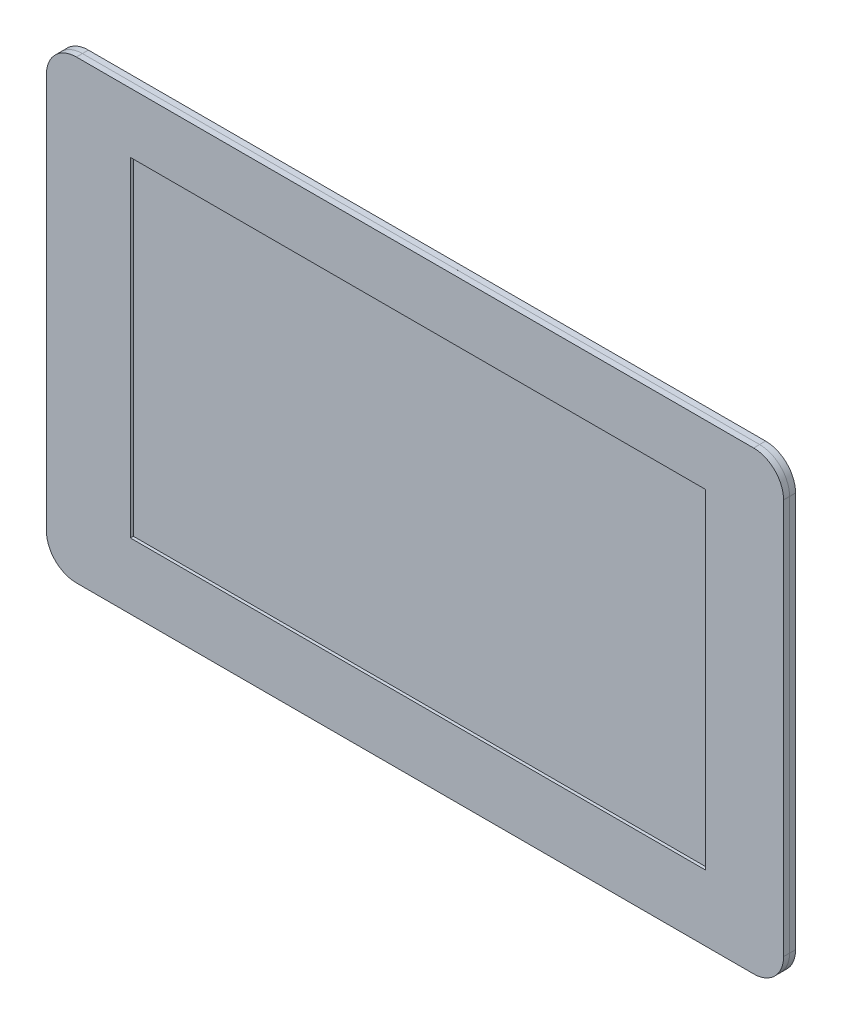
SolidWorks part; units mm, degrees
ref_plane "Front Plane" through (0, 0, 0) normal (0, 0, 1) x (1, 0, 0)
ref_plane "Top Plane" through (0, 0, 0) normal (0, 1, 0) x (1, 0, 0)
ref_plane "Right Plane" through (0, 0, 0) normal (1, 0, 0) x (0, 0, -1)
sketch "Sketch1" plane through (0, 0, 0) normal (0, 0, 1) x (1, 0, 0)
  line L1 (-56.5, -38) -> (56.5, -38)
  line L2 (-61.5, -33) -> (-61.5, 33)
  line L3 (-56.5, 38) -> (56.5, 38)
  line L4 (61.5, -33) -> (61.5, 33)
  line L5 (-61.5, -38) -> (61.5, 38) construction
  line L6 (-61.5, 38) -> (61.5, -38) construction
  line L7 (-47.5, 28) -> (48.5, 28)
  line L8 (-47.5, 28) -> (-47.5, -27)
  line L9 (-47.5, -27) -> (48.5, -27)
  line L10 (48.5, 28) -> (48.5, -27)
  arc A0 (-56.5, -38) -> (-61.5, -33) centre (-56.5, -33) cw
  arc A1 (56.5, -38) -> (61.5, -33) centre (56.5, -33) ccw
  arc A2 (56.5, 38) -> (61.5, 33) centre (56.5, 33) cw
  arc A3 (-61.5, 33) -> (-56.5, 38) centre (-56.5, 33) cw
  point P0 (0, 0)
  dimension "D3" = 5
  dimension "D1" = 123
  dimension "D2" = 76
  dimension "D4" = 96
  dimension "D5" = 55
  dimension "D6" = 10
  dimension "D7" = 13
extrude "Boss-Extrude1" add sketch "Sketch1" along normal blind 1
sketch "Sketch2" plane through (0, 0, 0) normal (0, 0, -1) x (-1, 0, 0)
  line L1 (-48.5, 28) -> (47.5, 28)
  line L2 (-48.5, 28) -> (-48.5, -27)
  line L3 (-48.5, -27) -> (47.5, -27)
  line L4 (47.5, 28) -> (47.5, -27)
extrude "Boss-Extrude2" add sketch "Sketch2" along normal mid plane 1 separate body
sketch "Sketch3" plane through (0, 0, 0) normal (0, 0, -1) x (-1, 0, 0)
  line L0 (52.5, 0) -> (61.5, 0) construction
  line L1 (-52.5, 36) -> (52.5, 36)
  line L2 (-52.5, 36) -> (-52.5, -36)
  line L3 (-52.5, -36) -> (52.5, -36)
  line L4 (52.5, 36) -> (52.5, -36)
  line L5 (0, -36) -> (0, -38) construction
  line L8 (61.5, -33) -> (61.5, 33)
  line L9 (56.5, 38) -> (-56.5, 38)
  line L10 (-61.5, 33) -> (-61.5, -33)
  line L11 (-56.5, -38) -> (56.5, -38)
  line L12 (61.5, -33) -> (61.5, 33)
  line L13 (56.5, 38) -> (-56.5, 38)
  line L14 (-61.5, 33) -> (-61.5, -33)
  line L15 (-56.5, -38) -> (56.5, -38)
  arc A4 (56.5, -38) -> (61.5, -33) centre (56.5, -33) ccw
  arc A5 (61.5, 33) -> (56.5, 38) centre (56.5, 33) ccw
  arc A6 (-56.5, 38) -> (-61.5, 33) centre (-56.5, 33) ccw
  arc A7 (-61.5, -33) -> (-56.5, -38) centre (-56.5, -33) ccw
  arc A8 (56.5, -38) -> (61.5, -33) centre (56.5, -33) ccw
  arc A9 (61.5, 33) -> (56.5, 38) centre (56.5, 33) ccw
  arc A10 (-56.5, 38) -> (-61.5, 33) centre (-56.5, 33) ccw
  arc A11 (-61.5, -33) -> (-56.5, -38) centre (-56.5, -33) ccw
  dimension "D2" = 105
  dimension "D3" = 72
  dimension "D1" = 0
extrude "Boss-Extrude3" add sketch "Sketch3" along normal blind 1 separate body
ref_plane "Plane1" through (46.5, 0, 0) normal (1, 0, 0) x (0, 0, -1)
sketch "Sketch4" plane through (46.5, 0, 0) normal (1, 0, 0) x (0, 0, -1)
  line L0 (1, 33) -> (1, -33) construction
  line L1 (1, -38) -> (1, -33) construction
  line L2 (1, -35.5) -> (6, -35.5) construction
  line L3 (3.5, -38) -> (1, -38) construction
  line L4 (6, -35.5) -> (6, -17.5)
  arc A0 (1, -35.5) -> (6, -35.5) centre (3.5, -35.5) ccw
  dimension "D1" = 2.5
  dimension "D2" = 18
extrude "Extrude-Thin2" add sketch "Sketch4" against normal blind 16 separate body thin
sketch "Sketch5" plane through (0, 0, -7) normal (0, 0, -1) x (-1, 0, 0)
  line L1 (-30.5, -17.5) -> (-34, -17.5)
  line L2 (-30.5, -17.5) -> (-30.5, -3.5)
  line L3 (-30.5, -3.5) -> (-34, -3.5)
  line L4 (-34, -17.5) -> (-34, -3.5)
  dimension "D1" = 3.5
  dimension "D2" = 14
extrude "Boss-Extrude4" add sketch "Sketch5" against normal blind 1
sketch "Sketch6" plane through (0, 0, 0) normal (0, 0, -1) x (-1, 0, 0)
  line L0 (-52.5, 36) -> (-52.5, -36) construction
  line L1 (-52.5, -35.5) -> (52.5, -35.5)
  line L2 (-52.5, -35.5) -> (-52.5, 31.5)
  line L3 (-52.5, 31.5) -> (52.5, 31.5)
  line L4 (52.5, -35.5) -> (52.5, 31.5)
  line L5 (52.5, -36) -> (52.5, 36) construction
  line L6 (-52.5, -36) -> (52.5, -36) construction
  dimension "D1" = 0.5
  dimension "D2" = 67
extrude "Boss-Extrude5" add sketch "Sketch6" along normal blind 3.2 separate body
